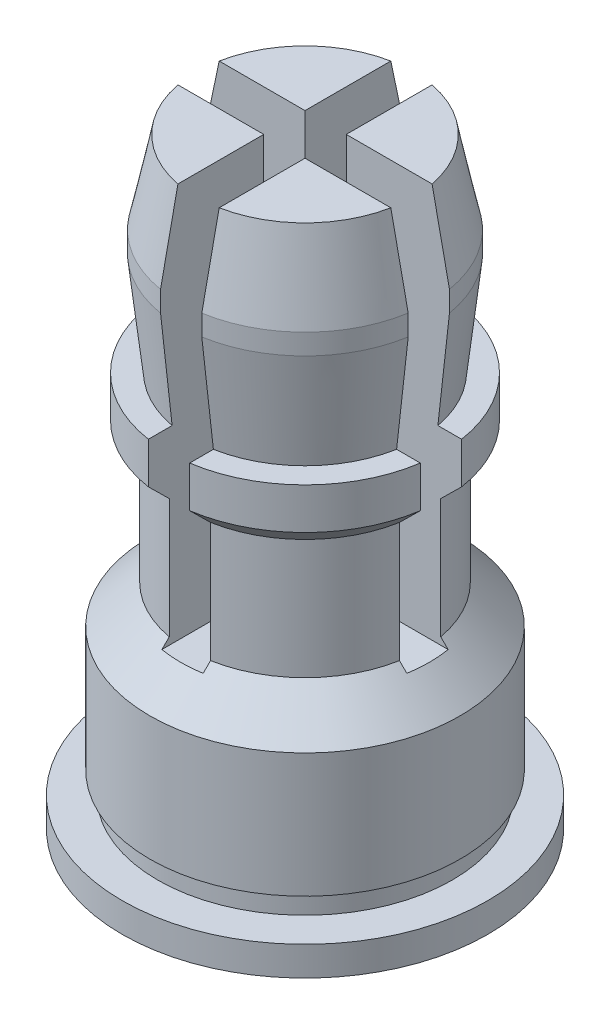
SolidWorks part; units mm, degrees
revolve "Body" add sketch "BodySke" angle 360 about L9
sketch "BodySke" plane through (0, 0, 0) normal (0, 0, 1) x (1, 0, 0)
  line L0 (2.5578, 0.508) -> (2.5578, 0.889)
  line L1 (2.6924, 3.0434) -> (2.0295, 3.7064)
  line L3 (2.0295, 3.7064) -> (2.0295, 5.7836)
  line L4 (0, 0) -> (3.175, 0)
  line L5 (3.175, 0) -> (3.175, 0.508)
  line L6 (3.175, 0.508) -> (2.5578, 0.508)
  line L7 (2.3876, 6.1417) -> (2.3876, 6.858)
  line L8 (2.6924, 0.889) -> (2.6924, 3.0434)
  line L9 (0, 0) -> (0, 17.145) construction
  line L10 (2.3876, 6.858) -> (1.9812, 6.858)
  line L11 (1.9812, 6.858) -> (2.1793, 8.6487)
  line L12 (2.1793, 8.6487) -> (2.1793, 9.0068)
  line L13 (2.1793, 9.0068) -> (1.8821, 10.4394)
  line L14 (1.8821, 10.4394) -> (0, 10.4394)
  line L15 (2.5578, 0.889) -> (2.6924, 0.889)
  line L17 (0, 10.4394) -> (0, 0)
  line L19 (2.3876, 6.1417) -> (2.0295, 5.7836)
  dimension "H_dia" = 6.35
  dimension "C_dia" = 5.3848
  dimension "Groove_dia" = 5.1156
  dimension "T_ht" = 0.508
  dimension "Groove_wid" = 0.381
  dimension "D_ht" = 3.5814
  dimension "Neck_dia" = 4.0589
  dimension "B_dia" = 4.7752
  dimension "B_ht" = 0.7163
  dimension "Panel_dia" = 3.9624
  dimension "Slip_dia" = 4.3586
  dimension "Tip_dia" = 3.7643
  dimension "Grip_ht" = 1.7907
  dimension "Slip_ht" = 0.3581
  dimension "Neck_len" = 3.1516
  dimension "D1" = 315
  dimension "Length" = 6.858
ref_plane "Plane1" through (0, 0, 0) normal (0, 0, 1) x (1, 0, 0)
ref_plane "Plane2" through (0, 0, 0) normal (0, 1, 0) x (1, 0, 0)
ref_plane "Plane3" through (0, 0, 0) normal (1, 0, 0) x (0, 0, -1)
sketch "SlitCutSke" plane through (0, 10.4394, 0) normal (0, 1, 0) x (-1, 0, 0)
  line L0 (-2.6685, 0.3581) -> (2.6685, 0.3581)
  line L1 (2.6685, -0.3581) -> (-2.6685, -0.3581)
  line L2 (-2.6685, 0.3581) -> (-2.6685, -0.3581)
  line L3 (2.6685, 0.3581) -> (2.6685, -0.3581)
  line L4 (-4.064, 0) -> (4.064, 0) construction
  circle A1 centre (0, 0) radius 2.6924 construction
extrude "SlitCut" cut sketch "SlitCutSke" against normal blind 6.86
pattern_circular "SlitCutPat" count 2 every 90 about axis through (0, 0, 0) along (0, 1, 0) of "SlitCut"
ref_plane "Plane4" through (0, -0.5486, 0) normal (0, 1, 0) x (-1, 0, 0)
equation "' \"Panel_dia@BodySke\" = 0.156"
equation "' \"Length@BodySke\" = 0.25"
equation "' \"B_dia@BodySke\" = 0.188"
equation "' \"C_dia@BodySke\" = 0.212"
equation "' \"D_ht@BodySke\" = 0.141"
equation "' \"H_dia@BodySke\" = 0.25"
equation "' \"T_ht@BodySke\" = 0.02"
equation "\"Tip_dia@BodySke\" = \"Panel_dia@BodySke\" * 0.95"
equation "\"Slip_dia@BodySke\" = \"Panel_dia@BodySke\" * 1.1"
equation "\"Slip_ht@BodySke\" = \"D_ht@BodySke\" * 0.1"
equation "\"Grip_ht@BodySke\" = \"D_ht@BodySke\" * 0.5"
equation "\"B_ht@BodySke\" = \"B_dia@BodySke\" * 0.15"
equation "\"Neck_dia@BodySke\" = \"B_dia@BodySke\" * 0.85"
equation "\"Neck_len@BodySke\" = \"B_dia@BodySke\" * 0.66"
equation "\"Groove_dia@BodySke\" = \"C_dia@BodySke\" * 0.95"
equation "\"Groove_wid@BodySke\" = \"T_ht@BodySke\" * 0.75"
equation "\"Width@SlitCutSke\" = \"B_ht@BodySke\""
equation "\"Depth@SlitCut\" = \"D_ht@BodySke\" + \"Neck_len@BodySke\" + 0.005"
